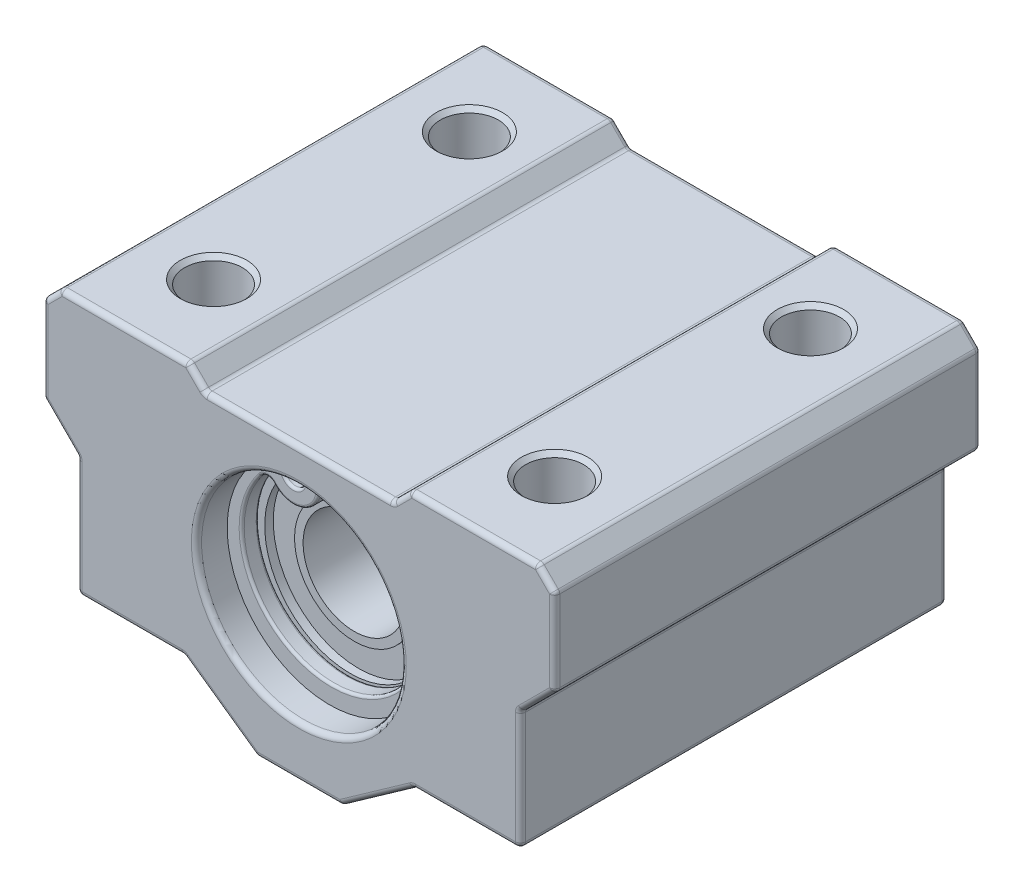
SolidWorks part; units mm, degrees
ref_plane "Piano frontale" through (0, 0, 0) normal (0, 0, 1) x (1, 0, 0)
ref_plane "Piano superiore" through (0, 0, 0) normal (0, 1, 0) x (1, 0, 0)
ref_plane "Piano destro" through (0, 0, 0) normal (1, 0, 0) x (0, 0, -1)
sketch "Schizzo1" plane through (0, 0, 0) normal (0, 0, 1) x (1, 0, 0)
  line L0 (0, 25) -> (0, -25) construction
  line L1 (-30, 0) -> (30, 0) construction
  line L2 (2.5, -9) -> (6.75, -6)
  line L3 (6.75, -6) -> (13, -6)
  line L4 (13, -6) -> (13, 1)
  line L5 (13, 1) -> (15, 3)
  line L6 (15, 3) -> (15, 8)
  line L8 (14, 9) -> (6.5, 9)
  line L9 (5.5, 8) -> (6.5, 9)
  line L10 (-15, 8) -> (15, 8) construction
  line L11 (-14, 9) -> (-15, 8)
  line L12 (14, 9) -> (15, 8)
  line L15 (-2.5, -9) -> (-6.75, -6)
  line L16 (-6.75, -6) -> (-13, -6)
  line L17 (-13, -6) -> (-13, 1)
  line L18 (-13, 1) -> (-15, 3)
  line L19 (-15, 3) -> (-15, 8)
  line L20 (-14, 9) -> (-6.5, 9)
  line L24 (-5.5, 8) -> (-6.5, 9)
  line L26 (-5.5, 8) -> (5.5, 8)
  line L27 (-2.5, -9) -> (2.5, -9)
  circle A0 centre (0, 0) radius 6
  point P3 (0, 0)
  point P6 (0, 0)
  point P8 (0, -9)
  point P17 (0, 8)
  point P55 (0, -7.6504)
  dimension "D4" = 12
  dimension "D5" = 5
  dimension "D2" = 5.5
  dimension "D1" = 45
  dimension "D3" = 35.218
  dimension "D6" = 1
  dimension "D7" = 7.5
  dimension "D8" = 26
  dimension "G" = 15
  dimension "T" = 6
  dimension "F" = 18
  dimension "W" = 30
  dimension "E" = 15
  dimension "h" = 9
  dimension "L1" = 8
extrude "Estrusione-Estrusione1" add sketch "Schizzo1" along normal mid plane 25
hole_wizard "Foro per Vite M4-1" positions "Schizzo3" profile "Schizzo4" hole size "M4" standard "ISO" end condition through all
sketch "Schizzo3" plane through (0, 9, 0) normal (0, 1, 0) x (1, 0, 0)
  line L3 (0, 0) -> (-18, 0) construction
  line L5 (0, 0) -> (0, 17) construction
  line L6 (-15, -12.5) -> (-15, 12.5) construction
  line L7 (-6.5, 12.5) -> (-14, 12.5) construction
  point P0 (-10, 7.5)
  dimension "D1" = 10
  dimension "D2" = 7.5
  dimension "D3" = 5
  dimension "D4" = 5
sketch "Schizzo4" plane through (-10, 9, -7.5) normal (1, 0, 0) x (0, 0, 1)
  line L0 (0, 0) -> (0, 18)
  line L1 (0, 18) -> (1.7, 18)
  line L2 (1.7, 18) -> (1.7, 0)
  line L5 (1.7, 0) -> (0, 0)
  line L11 (0, -6.35) -> (0, 107.95) construction
  dimension "Thru Hole Dia." = 3.4
  dimension "Thru Hole Depth" = 18
pattern_linear "Ripetizione a L1" count 2 spacing 20 along (1, 0, 0) count 2 spacing 15 along (0, 0, 1) of "Foro per Vite M4-1"
chamfer "Smusso1" distance 0.25 angle 45 4 edges at (-10, 9, 9.2) (10, 9, 9.2) (10, 9, -5.8) (-10, 9, -5.8)
chamfer "Smusso2" distance 0.5 angle 45 4 edges at (10, -6, -5.8) (10, -6, 9.2) (-11.7, -6, 7.5) (-11.7, -6, -7.5)
sketch "Schizzo6" plane through (0, 0, 0) normal (1, 0, 0) x (0, 0, -1)
  line L0 (-20, 0) -> (20, 0) construction
  line L3 (-9.5, 5) -> (-9, 5)
  line L4 (-9, 5) -> (-9, 3.5)
  line L9 (9, 5) -> (9, 3.5)
  line L13 (-9.5, 6) -> (-9.5, 5)
  line L14 (0, -1.396) -> (0, 15.3751) construction
  line L15 (-9.5, 6) -> (9.5, 6)
  line L18 (9.5, 6) -> (9.5, 5)
  line L19 (9.5, 5) -> (9, 5)
  line L20 (-9, 3.5) -> (-9.25, 3.5)
  line L21 (9, 3.5) -> (9.25, 3.5)
  line L22 (-9.25, 3.5) -> (-9.25, 0)
  line L23 (9.25, 3.5) -> (9.25, 0)
  line L24 (9.25, 0) -> (-9.25, 0)
  point P3 (0, 0)
  point P7 (0, 6)
  dimension "D1" = 19
  dimension "D2" = 1
  dimension "D3" = 0.5
  dimension "D4" = 0.25
  dimension "D5" = 3.5
  dimension "D6" = 6
revolve "Rivoluzione1" add sketch "Schizzo6" angle 360 about L0
fillet "Raccordo1" radius 0.3 56 edges at (-6.5, 9, 0) (14, 9, 0) (-5.5, 8, 0) (6.5, 9, 0) (5.5, 8, 0) (-14, 9, 0) (-15, 8, 0) (-15, 3, 0) (-13, 1, 0) (-13, -6, 0) (-6.75, -6, 0) (15, 8, 0) (15, 3, 0) (13, -6, 0) (13, 1, 0) (6.75, -6, 0) (-2.5, -9, 0) (2.5, -9, 0) (6, 0, 12.5) (-4.625, -7.5, 12.5) (-9.875, -6, 12.5) (-13, -2.5, 12.5) (-14, 2, 12.5) (-15, 5.5, 12.5) (-14.5, 8.5, 12.5) (-10.25, 9, 12.5) (-6, 8.5, 12.5) (0, 8, 12.5) (6, 8.5, 12.5) (10.25, 9, 12.5) (14.5, 8.5, 12.5) (15, 5.5, 12.5) (14, 2, 12.5) (13, -2.5, 12.5) (9.875, -6, 12.5) (4.625, -7.5, 12.5) (0, -9, 12.5) (6, 0, -12.5) (4.625, -7.5, -12.5) (9.875, -6, -12.5) (13, -2.5, -12.5) (14, 2, -12.5) (15, 5.5, -12.5) (14.5, 8.5, -12.5) (10.25, 9, -12.5) (6, 8.5, -12.5) (0, 8, -12.5) (-6, 8.5, -12.5) (-10.25, 9, -12.5) (-14.5, 8.5, -12.5) (-15, 5.5, -12.5) (-14, 2, -12.5) (-13, -2.5, -12.5) (-9.875, -6, -12.5) (-4.625, -7.5, -12.5) (0, -9, -12.5)
sketch "Schizzo8" plane through (0, 0, 0) normal (0, 0, 1) x (1, 0, 0)
  circle A0 centre (0, 0) radius 3
  dimension "D1" = 6
extrude "Taglio-Estrusione2" cut sketch "Schizzo8" against normal through all both and the other way through all
sketch "Schizzo7" plane through (0, 0, 0) normal (0, 0, 1) x (1, 0, 0)
  circle A0 centre (0, 0) radius 6.8
  dimension "D1" = 13.6
extrude "Taglio-Estrusione1" cut sketch "Schizzo7" along normal blind 1.1 from offset 9.6
mirror "Specchia1" about plane through (0, 0, 0) normal (0, 0, 1) of "Taglio-Estrusione1"
sketch "Schizzo9" plane through (0, 0, 0) normal (0, 0, 1) x (1, 0, 0)
  line L0 (-9.6311, 0) -> (8.8612, 0) construction
  line L1 (0, 22.577) -> (0, -2.423) construction
  line L2 (0, 0) -> (11.179, 22.4215) construction
  line L3 (0, 0) -> (-11.179, 22.4215) construction
  line L4 (-1.7195, 0.25) -> (1.6027, 0.25) construction
  arc A11 (-2.9003, 5.8171) -> (2.9003, 5.8171) centre (0, 0) ccw
  arc A12 (-4.141, 3.4771) -> (4.141, 3.4771) centre (0, 0.25) ccw
  arc A13 (-3.3677, 3.496) -> (-2.9003, 5.8171) centre (-2.231, 4.4747) ccw
  arc A14 (3.3677, 3.496) -> (2.9003, 5.8171) centre (2.231, 4.4747) cw
  circle A15 centre (-2.231, 4.4747) radius 0.6
  circle A16 centre (2.231, 4.4747) radius 0.6
  arc A17 (3.3677, 3.496) -> (4.141, 3.4771) centre (3.7467, 3.1698) cw
  arc A18 (-3.3677, 3.496) -> (-4.141, 3.4771) centre (-3.7467, 3.1698) ccw
  dimension "D1" = 0.25
  dimension "D2" = 53
  dimension "D3" = 13
  dimension "D6" = 3
  dimension "D5" = 10.5
  dimension "D7" = 1.2
  dimension "D8" = 0.5
  dimension "D4" = 26.5
extrude "Estrusione-Estrusione2" add sketch "Schizzo9" along normal blind 1 from offset 9.6 separate body
pattern_linear "Ripetizione a L2" count 2 spacing 20.2 along (0, 0, -1) of "Estrusione-Estrusione2"
fillet "Raccordo4" radius 0.15 16 edges at (2.831, 4.4747, 10.6) (-1.631, 4.4747, 10.6) (0, -6.5, 10.6) (-0.7605, 4.1785, 10.6) (0, -5, 10.6) (0.7605, 4.1785, 10.6) (2.831, 4.4747, 9.6) (0, -5, 9.6) (-0.7605, 4.1785, 9.6) (0, -6.5, 9.6) (0.7605, 4.1785, 9.6) (-1.631, 4.4747, 9.6) (-3.7589, 3.6696, 10.6) (3.7589, 3.6696, 10.6) (3.7589, 3.6696, 9.6) (-3.7589, 3.6696, 9.6)
fillet "Raccordo5" radius 0.15 16 edges at (2.831, 4.4747, -9.6) (-1.631, 4.4747, -9.6) (0, -6.5, -9.6) (-0.7605, 4.1785, -9.6) (0, -5, -9.6) (0.7605, 4.1785, -9.6) (2.831, 4.4747, -10.6) (0, -5, -10.6) (-0.7605, 4.1785, -10.6) (0, -6.5, -10.6) (0.7605, 4.1785, -10.6) (-1.631, 4.4747, -10.6) (-3.7589, 3.6696, -9.6) (3.7589, 3.6696, -9.6) (3.7589, 3.6696, -10.6) (-3.7589, 3.6696, -10.6)
